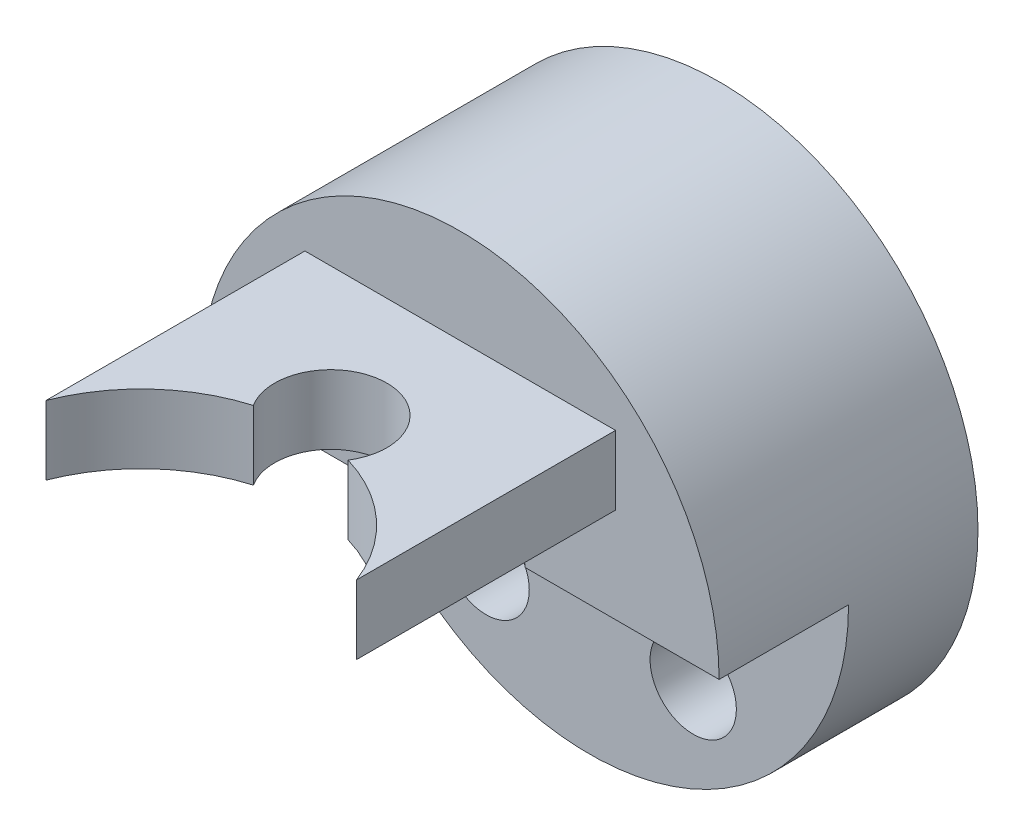
SolidWorks part; units mm, degrees
ref_plane "Спереди" through (0, 0, 0) normal (0, 0, 1) x (1, 0, 0)
ref_plane "Сверху" through (0, 0, 0) normal (0, 1, 0) x (1, 0, 0)
ref_plane "Справа" through (0, 0, 0) normal (1, 0, 0) x (0, 0, -1)
sketch "Эскиз1" plane through (0, 0, 0) normal (0, 0, 1) x (1, 0, 0)
  circle A0 centre (0, 0) radius 30
  dimension "D1" = 60
extrude "Бобышка-Вытянуть1" add sketch "Эскиз1" along normal blind 15
sketch "Эскиз2" plane through (0, 0, 15) normal (0, 0, 1) x (1, 0, 0)
  line L0 (-30, 0) -> (30, 0)
  circle A0 centre (0, 0) radius 30 construction
  arc A1 (30, 0) -> (-30, 0) centre (0, 0) ccw
extrude "Бобышка-Вытянуть2" add sketch "Эскиз2" along normal blind 15
sketch "Эскиз3" plane through (0, 0, 30) normal (0, 0, 1) x (1, 0, 0)
  circle A0 centre (0, 0) radius 7.5
  dimension "D1" = 15
extrude "Вырез-Вытянуть1" cut sketch "Эскиз3" against normal through all
sketch "Эскиз4" plane through (0, 0, 30) normal (0, 0, 1) x (1, 0, 0)
  line L0 (0, 0) -> (0, 30) construction
  line L1 (-18, 11) -> (18, 11)
  line L2 (-18, 11) -> (-18, 19)
  line L3 (-18, 19) -> (18, 19)
  line L4 (18, 11) -> (18, 19)
  line L5 (-18, 11) -> (18, 19) construction
  line L6 (-18, 19) -> (18, 11) construction
  arc A0 (30, 0) -> (-30, 0) centre (0, 0) ccw construction
  point P0 (0, 15)
  dimension "D1" = 8
  dimension "D2" = 36
extrude "Бобышка-Вытянуть3" add sketch "Эскиз4" along normal blind 30
sketch "Эскиз5" plane through (0, 11, 0) normal (0, -1, 0) x (-1, 0, 0)
  circle A0 centre (0, -67) radius 19.3132
  dimension "D1" = 67
sketch "Эскиз6" plane through (0, 11, 0) normal (0, -1, 0) x (-1, 0, 0)
  line L0 (0, -60) -> (0, -30) construction
  line L1 (18, -60) -> (-18, -60) construction
  line L2 (-7.5, -30) -> (7.5, -30) construction
  circle A0 centre (0, -45) radius 6.5
  dimension "D1" = 13
extrude "Вырез-Вытянуть3" cut sketch "Эскиз6" against normal through all
extrude "Вырез-Вытянуть4" cut sketch "Эскиз5" against normal through all contours A0
sketch "Эскиз7" plane through (0, 0, 15) normal (0, 0, 1) x (1, 0, 0)
  line L0 (0, -30) -> (0, 0) construction
  line L1 (-12, -17) -> (12, -17) construction
  arc A0 (-30, 0) -> (30, 0) centre (0, 0) ccw construction
  circle A1 centre (-12, -17) radius 5
  circle A2 centre (12, -17) radius 5
  point P10 (0, -17)
  dimension "D1" = 10
  dimension "D2" = 17
  dimension "D3" = 24
extrude "Вырез-Вытянуть5" cut sketch "Эскиз7" against normal through all
